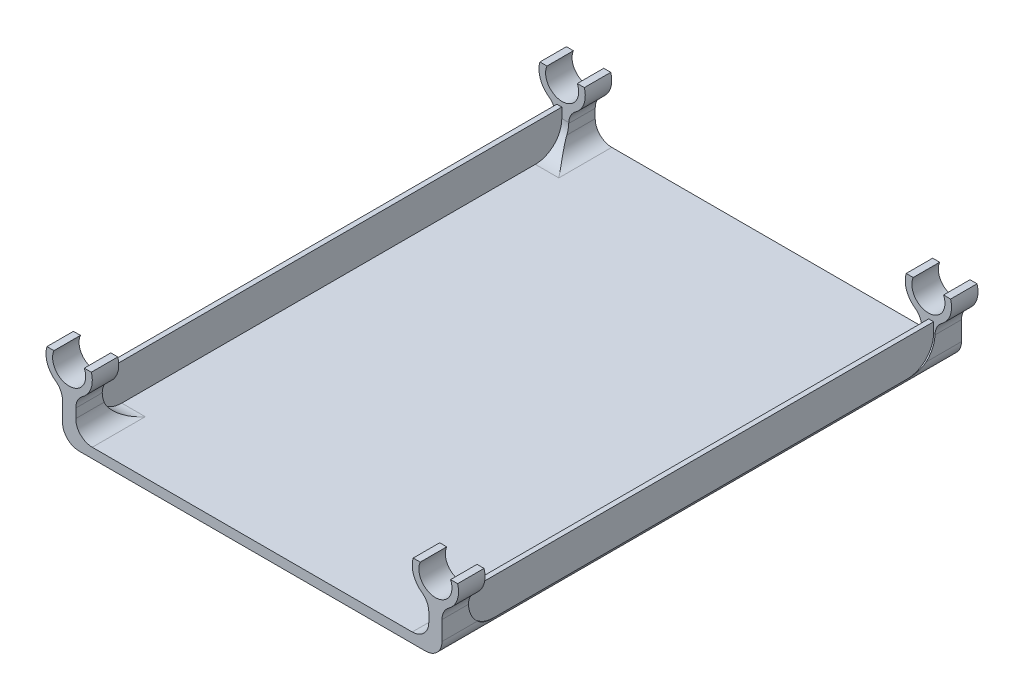
SolidWorks part; units mm, degrees
material "PLA 100% Infill"
ref_plane "Front Plane" through (0, 0, 0) normal (0, 0, 1) x (1, 0, 0)
ref_plane "Top Plane" through (0, 0, 0) normal (0, 1, 0) x (1, 0, 0)
ref_plane "Right Plane" through (0, 0, 0) normal (1, 0, 0) x (0, 0, -1)
sketch "Sketch1" plane through (0, 0, 0) normal (0, 0, 1) x (1, 0, 0)
  line L0 (-57.35, 0) -> (-57.35, 20.5) construction
  line L1 (0, 0) -> (-114.7, 0)
  line L2 (0, 0) -> (0, 2)
  line L3 (-4, 3) -> (-110.7, 3)
  line L4 (-114.7, 0) -> (-114.7, 2)
  line L5 (-53.0777, 20.5) -> (-61.6223, 20.5) construction
  line L6 (-114.7, 2) -> (-114.7, 13.7918)
  line L7 (-114.7, 13.7918) -> (-110.7, 13.7918) construction
  line L8 (-110.7, 13.7918) -> (-110.7, 3)
  line L9 (-119.4082, 22.5) -> (-117.2826, 22.5)
  line L10 (-108.1174, 22.5) -> (-105.9918, 22.5)
  line L11 (0, 2) -> (0, 13.7918)
  line L12 (-4, 13.7918) -> (-4, 3)
  line L13 (4.7082, 22.5) -> (2.5826, 22.5)
  line L14 (-6.5826, 22.5) -> (-8.7082, 22.5)
  line L15 (0, 13.7918) -> (0, 2)
  line L16 (-80.7757, 3) -> (-81.6086, 3)
  arc A0 (-117.2826, 22.5) -> (-108.1174, 22.5) centre (-112.7, 20.5) ccw
  arc A1 (-119.4082, 22.5) -> (-114.7, 13.7918) centre (-112.7, 20.5) ccw
  arc A2 (4.7082, 22.5) -> (0, 13.7918) centre (-2, 20.5) cw
  arc A3 (2.5826, 22.5) -> (-6.5826, 22.5) centre (-2, 20.5) cw
  arc A4 (-4, 13.7918) -> (-8.7082, 22.5) centre (-2, 20.5) cw
  arc A5 (-110.7, 13.7918) -> (-105.9918, 22.5) centre (-112.7, 20.5) ccw
  dimension "D2" = 10
  dimension "D6" = 3
  dimension "D1" = 20.5
  dimension "D3" = 114.7
  dimension "D4" = 2
  dimension "D5" = 4
  dimension "D7" = 2
  dimension "D8" = 2
extrude "Boss-Extrude1" add sketch "Sketch1" along normal blind 157 contours L8 A5 L10 A0 L9 A1 L6 L4 L1 L2 L11 A2 L13 A3 L14 A4 L12 L3
fillet "Fillet1" radius 5 8 edges at (0, 0, 78.5) (-114.7, 0, 78.5) (0, 13.7918, 78.5) (-4, 13.7918, 78.5) (-4, 3, 78.5) (-110.7, 3, 78.5) (-114.7, 13.7918, 78.5) (-110.7, 13.7918, 78.5)
sketch "Sketch2" plane through (-114.7, 0, 0) normal (-1, 0, 0) x (0, 0, 1)
  line L0 (157, 22.5) -> (0, 22.5) construction
  line L1 (8, 22.5) -> (149, 22.5)
  line L2 (8, 22.5) -> (8, 3)
  line L4 (149, 22.5) -> (149, 3)
  line L5 (0, 0) -> (-6.1147, 13.5)
  line L6 (-6.1147, 13.5) -> (-2.1147, 13.5)
  line L7 (-2.1147, 13.5) -> (1.8573, 4.7307)
  line L8 (8, 3) -> (149, 3)
  line L9 (157, 3) -> (0, 3) construction
  line L18 (78.5, 22.5) -> (78.5, 0) construction
  line L21 (159.1147, 13.5) -> (155.1427, 4.7307)
  line L22 (163.1147, 13.5) -> (159.1147, 13.5)
  line L23 (157, 0) -> (163.1147, 13.5)
  line L24 (0, 0) -> (1.8573, 4.7307)
  line L25 (155.1427, 4.7307) -> (157, 0)
  line L26 (157, 0) -> (0, 0) construction
  line L27 (0, 22.5) -> (0, 14.8144) construction
  dimension "D1" = 8
  dimension "D6" = 4
  dimension "D7" = 13.5
extrude "Cut-Extrude1" cut sketch "Sketch2" against normal through all and the other way through all
fillet "Fillet5" radius 8 4 edges at (-4.7087, 3, 8) (-4.7087, 3, 149) (-109.9913, 3, 149) (-109.9913, 3, 8)
ref_plane "Plane1" through (-114.2826, 0, 0) normal (-1, 0, 0) x (0, 0, 1)
sketch "Sketch4" plane through (0, 0, 8) normal (0, 0, 1) x (1, 0, 0)
  line L4 (-105.7, 3) -> (-114.2826, 3) construction
  line L5 (-114.2826, 62.6258) -> (-114.2826, -62.6258) construction
  line L6 (-57.35, 3) -> (-57.35, 0) construction
  line L7 (-114.2826, 14) -> (-112.7947, 14)
  line L8 (-114.2826, 14) -> (-114.2826, 3)
  line L9 (-114.2826, 3) -> (-112.7947, 3)
  line L10 (-112.7947, 14) -> (-112.7947, 3)
  line L11 (-114.2826, 14) -> (-112.7947, 3) construction
  line L12 (-114.2826, 3) -> (-112.7947, 14) construction
  line L13 (-9, 3) -> (-105.7, 3) construction
  line L14 (-5, 0) -> (-109.7, 0) construction
  line L15 (-1.9053, 14) -> (-1.9053, 3)
  line L16 (-0.4174, 3) -> (-1.9053, 3)
  line L17 (-0.4174, 14) -> (-0.4174, 3)
  line L18 (-0.4174, 14) -> (-1.9053, 14)
  arc A0 (-114.7, 5) -> (-109.7, 0) centre (-109.7, 5) ccw construction
  point P12 (-113.5386, 8.5)
  dimension "D1" = 11
extrude "Boss-Extrude5" add sketch "Sketch4" along normal up to surface (141 mm away)
